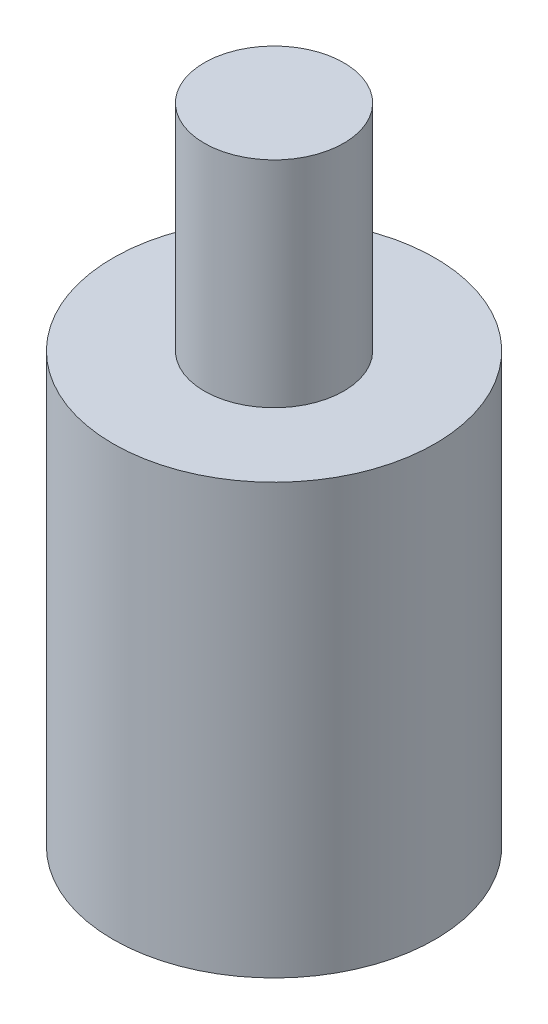
SolidWorks part; units mm, degrees
ref_plane "Front Plane" through (0, 0, 0) normal (0, 0, 1) x (1, 0, 0)
ref_plane "Top Plane" through (0, 0, 0) normal (0, 1, 0) x (1, 0, 0)
ref_plane "Right Plane" through (0, 0, 0) normal (1, 0, 0) x (0, 0, -1)
sketch "Sketch1" plane through (0, 0, 0) normal (0, 1, 0) x (1, 0, 0)
  circle A0 centre (0, 0) radius 3
  dimension "D1" = 6
extrude "Boss-Extrude2" add sketch "Sketch1" along normal blind 8
sketch "Sketch3" plane through (0, 8, 0) normal (0, 1, 0) x (1, 0, 0)
  circle A0 centre (0, 0) radius 1.3
  dimension "D1" = 2.6
extrude "Boss-Extrude3" add sketch "Sketch3" along normal blind 4
sketch "Sketch4" plane through (0, 0, 0) normal (0, -1, 0) x (1, 0, 0)
  circle A0 centre (0, 0) radius 1.75
  dimension "D1" = 3.5
extrude "Cut-Extrude1" cut sketch "Sketch4" against normal blind 6
